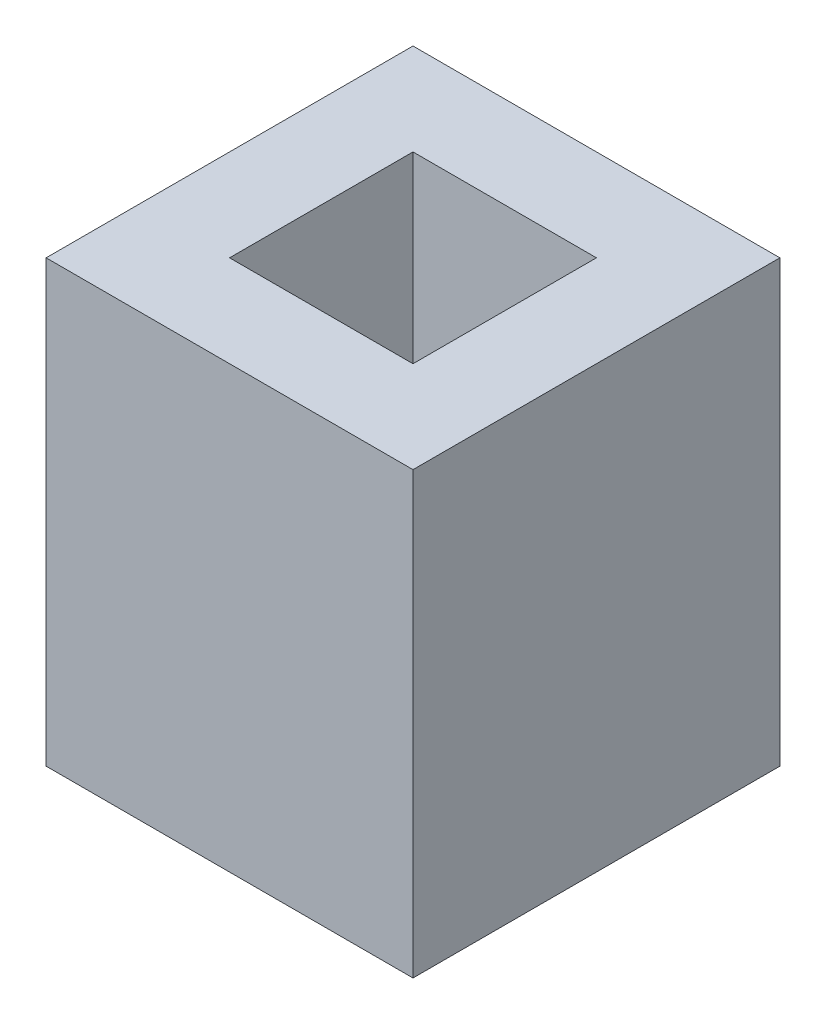
SolidWorks part; units mm, degrees
ref_plane "Front Plane" through (0, 0, 0) normal (0, 0, 1) x (1, 0, 0)
ref_plane "Top Plane" through (0, 0, 0) normal (0, 1, 0) x (1, 0, 0)
ref_plane "Right Plane" through (0, 0, 0) normal (1, 0, 0) x (0, 0, -1)
sketch "Sketch2" plane through (0, 0, 0) normal (0, 1, 0) x (1, 0, 0)
  line L1 (0, 0) -> (10, 0)
  line L2 (0, 0) -> (0, 10)
  line L3 (0, 10) -> (10, 10)
  line L4 (10, 0) -> (10, 10)
  line L5 (2.5, 7.5) -> (7.5, 7.5)
  line L6 (2.5, 7.5) -> (2.5, 2.5)
  line L7 (2.5, 2.5) -> (7.5, 2.5)
  line L8 (7.5, 7.5) -> (7.5, 2.5)
  point P9 (10, 5)
  dimension "D1" = 10
  dimension "D2" = 10
  dimension "D3" = 5
  dimension "D4" = 5
  dimension "D5" = 2.5
  dimension "D6" = 2.5
extrude "Boss-Extrude1" add sketch "Sketch2" along normal blind 12
